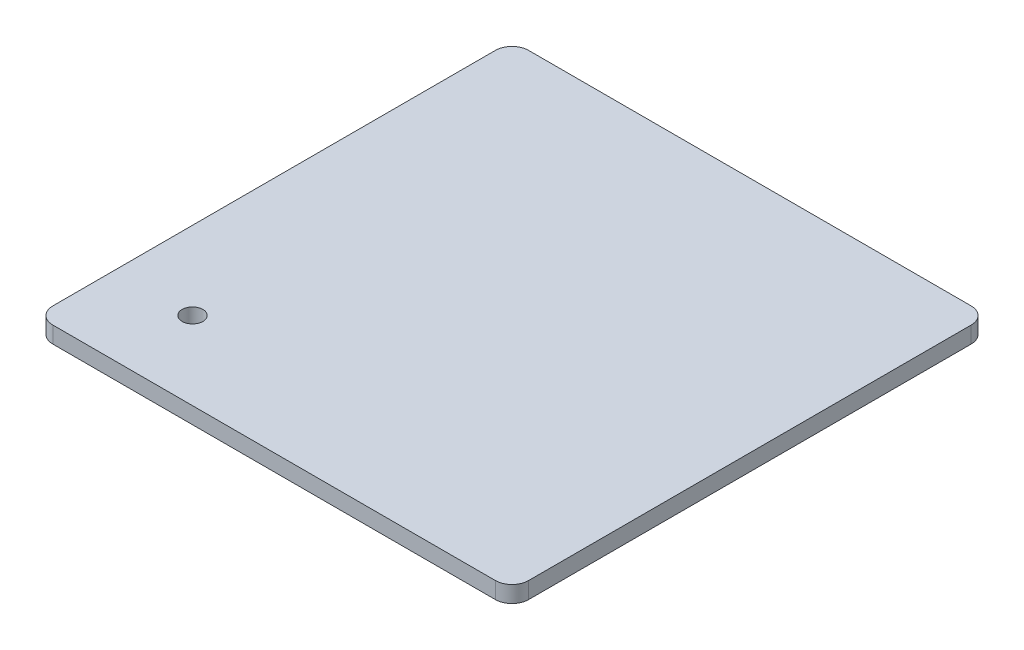
SolidWorks part; units mm, degrees
material "6061 Alloy"
ref_plane "Front Plane" through (0, 0, 0) normal (0, 0, 1) x (1, 0, 0)
ref_plane "Top Plane" through (0, 0, 0) normal (0, 1, 0) x (1, 0, 0)
ref_plane "Right Plane" through (0, 0, 0) normal (1, 0, 0) x (0, 0, -1)
ref_plane "Plane1" through (0, 0, 0) normal (0, 1, 0) x (1, 0, 0)
sketch "Sketch1" plane through (0, 0, 0) normal (0, 1, 0) x (1, 0, 0)
  line L1 (0, 0) -> (91.35, 0)
  line L2 (0, 0) -> (0, 91.35)
  line L3 (0, 91.35) -> (91.35, 91.35)
  line L4 (91.35, 0) -> (91.35, 91.35)
  dimension "D1" = 91.35
  dimension "D2" = 91.35
extrude "Boss-Extrude1" add sketch "Sketch1" along normal blind 3.175
ref_plane "Plane2" through (0, 3.175, 0) normal (0, 1, 0) x (1, 0, 0)
sketch "Sketch2" plane through (0, 3.175, 0) normal (0, 1, 0) x (1, 0, 0)
  line L0 (0, 0) -> (91.35, 0) construction
  line L1 (0, 91.35) -> (0, 0) construction
  circle A0 centre (15, 15) radius 2
  dimension "D3" = 4
  dimension "D1" = 15
  dimension "D2" = 15
extrude "Cut-Extrude1" cut sketch "Sketch2" against normal through all
fillet "Fillet1" radius 3.175 4 edges at (0, 1.5875, 0) (91.35, 1.5875, 0) (91.35, 1.5875, -91.35) (0, 1.5875, -91.35)
